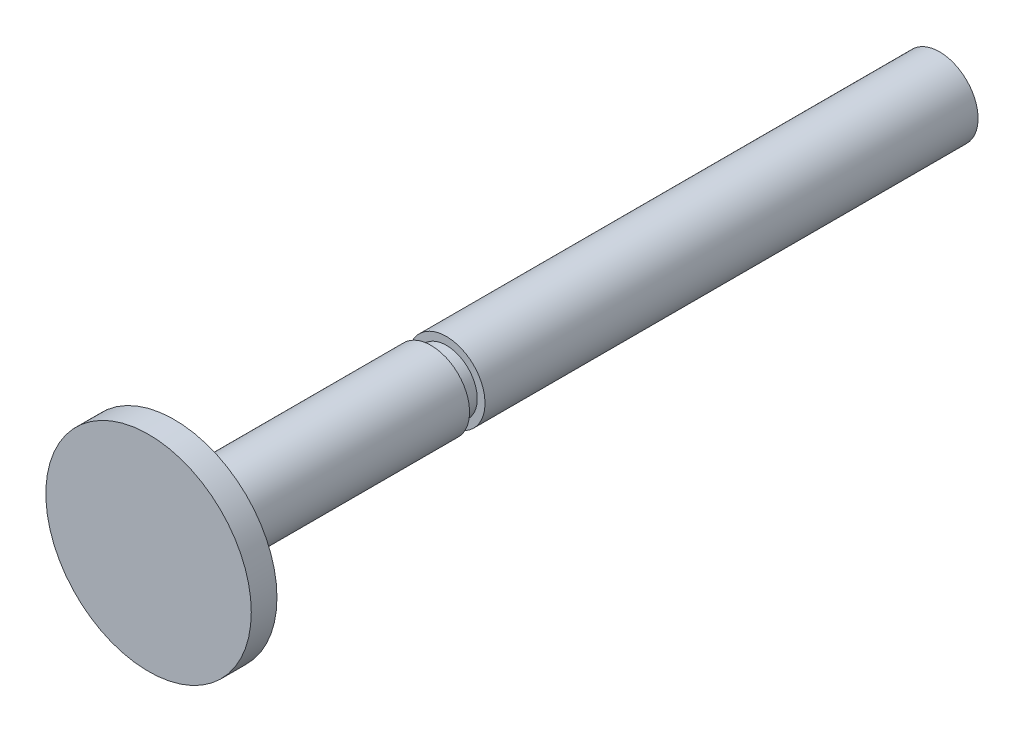
SolidWorks part; units mm, degrees
ref_plane "Front Plane" through (0, 0, 0) normal (0, 0, 1) x (1, 0, 0)
ref_plane "Top Plane" through (0, 0, 0) normal (0, 1, 0) x (1, 0, 0)
ref_plane "Right Plane" through (0, 0, 0) normal (1, 0, 0) x (0, 0, -1)
sketch "Sketch1" plane through (0, 0, 0) normal (0, 0, 1) x (1, 0, 0)
  circle A0 centre (0, 0) radius 2
  dimension "D1" = 4
extrude "Boss-Extrude1" add sketch "Sketch1" along normal blind 0.5
sketch "Sketch2" plane through (0, 0, 0) normal (0, 0, -1) x (-1, 0, 0)
  circle A0 centre (0, 0) radius 0.75
  dimension "D1" = 1.5
extrude "Boss-Extrude2" add sketch "Sketch2" along normal blind 5
sketch "Sketch3" plane through (0, 0, -5) normal (0, 0, -1) x (-1, 0, 0)
  circle A0 centre (0, 0) radius 0.6
  dimension "D1" = 1.2
extrude "Boss-Extrude3" add sketch "Sketch3" along normal blind 0.3
sketch "Sketch4" plane through (0, 0, -5.3) normal (0, 0, -1) x (-1, 0, 0)
  circle A0 centre (0, 0) radius 0.75
  dimension "D1" = 1.5
extrude "Boss-Extrude4" add sketch "Sketch4" along normal blind 9.6
